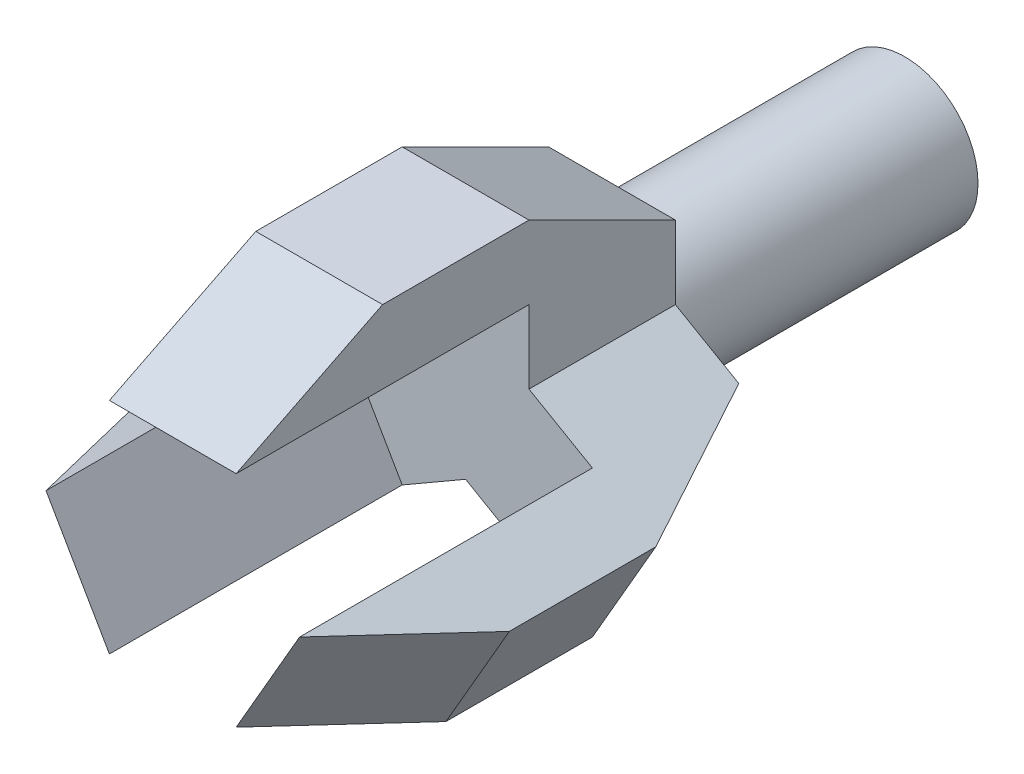
SolidWorks part; units mm, degrees
material "Brass"
ref_plane "Front Plane" through (0, 0, 0) normal (0, 0, 1) x (1, 0, 0)
ref_plane "Top Plane" through (0, 0, 0) normal (0, 1, 0) x (1, 0, 0)
ref_plane "Right Plane" through (0, 0, 0) normal (1, 0, 0) x (0, 0, -1)
sketch "Sketch1" plane through (0, 0, 0) normal (0, 0, 1) x (1, 0, 0)
  circle A0 centre (0, 0) radius 50
  dimension "D1" = 100
extrude "Boss-Extrude1" add sketch "Sketch1" along normal blind 200
sketch "Sketch2" plane through (0, 0, 200) normal (0, 0, 1) x (1, 0, 0)
  line L0 (43.3013, 25) -> (43.3013, 75)
  line L1 (0, 0) -> (0, 227.9839) construction
  line L3 (-43.3013, 25) -> (43.3013, 25) construction
  line L4 (43.3013, 75) -> (-43.3013, 75)
  line L5 (-43.3013, 75) -> (-43.3013, 25)
  line L12 (-43.3013, 25) -> (0, 0)
  line L13 (0, 0) -> (43.3013, 25)
  circle A1 centre (0, 0) radius 50 construction
  point P3 (0, 75)
  dimension "D1" = 60
  dimension "D2" = 120
  dimension "D3" = 75
  dimension "D4" = 25
extrude "Boss-Extrude2" add sketch "Sketch2" along normal blind 100
sketch "Sketch3" plane through (-43.3013, 0, 0) normal (-1, 0, 0) x (0, 1, 0)
  line L0 (75, -300) -> (75, -200) construction
  line L1 (75, -200) -> (75, -500)
  line L2 (75, -200) -> (125, -300)
  line L3 (125, -300) -> (125, -400)
  line L4 (125, -400) -> (75, -500)
  line L5 (75, -200) -> (25, -200) construction
  dimension "D1" = 50
  dimension "D2" = 100
  dimension "D3" = 100
  dimension "D4" = 100
extrude "Boss-Extrude4" add sketch "Sketch3" against normal up to surface (86.6025 mm away) up to face at (43.3013, 50, 250)
pattern_circular "CirPattern1" count 3 over 360 about axis through (0, 0, 0) along (0, 0, 1) of "Boss-Extrude2", "Boss-Extrude4"
